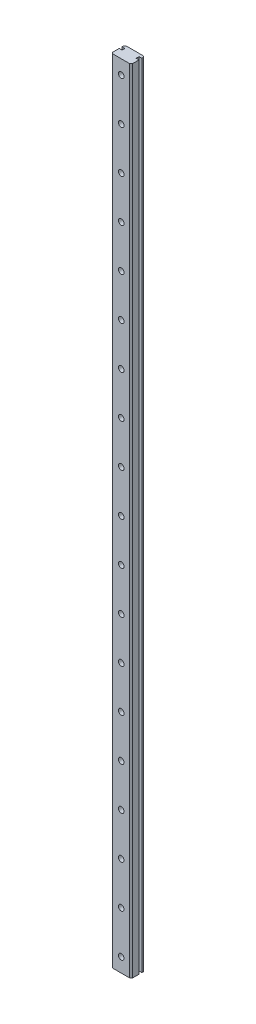
SolidWorks part; units mm, degrees
material "AISI 304"
ref_plane "前视基准面" through (0, 0, 0) normal (0, 0, 1) x (1, 0, 0)
ref_plane "上视基准面" through (0, 0, 0) normal (0, 1, 0) x (1, 0, 0)
ref_plane "右视基准面" through (0, 0, 0) normal (1, 0, 0) x (0, 0, -1)
other "Configuration Table"
sketch "草图1" plane through (0, 0, 0) normal (0, 1, 0) x (1, 0, 0)
  line L0 (0, 0) -> (0, 7.157) construction
  line L1 (-3.5, -2.4) -> (3.5, -2.4)
  line L2 (-3.5, -2.4) -> (-3.5, 2.4)
  line L3 (-3.5, 2.4) -> (3.5, 2.4)
  line L4 (3.5, -2.4) -> (3.5, 2.4)
  line L5 (-3.5, -2.4) -> (3.5, 2.4) construction
  line L6 (-3.5, 2.4) -> (3.5, -2.4) construction
  line L7 (3.5, 1.4) -> (2.5, 1.4)
  line L8 (2.5, 1.4) -> (2.5, 0.4)
  line L9 (2.5, 0.4) -> (3.5, 0.4)
  line L10 (-2.5, 0.4) -> (-3.5, 0.4)
  line L11 (-2.5, 1.4) -> (-2.5, 0.4)
  line L12 (-3.5, 1.4) -> (-2.5, 1.4)
  point P0 (0, 0)
  dimension "D1" = 7
  dimension "D2" = 4.8
  dimension "D3" = 1
  dimension "D4" = 1
  dimension "D5" = 1
extrude "凸台-拉伸1" add sketch "草图1" along normal blind 280 contours L2 L12 L11 L10 L1 L4 L9 L8 L7 L3
sketch "草图2" plane through (0, 0, -2.4) normal (0, 0, -1) x (-1, 0, 0)
  line L0 (3.5, 0) -> (-3.5, 0) construction
  line L1 (-3.5, 280) -> (-3.5, 0) construction
  circle A0 centre (0, 5) radius 1
  circle A1 centre (0, 20) radius 1
  circle A2 centre (0, 35) radius 1
  circle A3 centre (0, 50) radius 1
  circle A4 centre (0, 65) radius 1
  circle A5 centre (0, 80) radius 1
  circle A6 centre (0, 95) radius 1
  circle A7 centre (0, 110) radius 1
  circle A8 centre (0, 125) radius 1
  circle A9 centre (0, 140) radius 1
  circle A10 centre (0, 155) radius 1
  circle A11 centre (0, 170) radius 1
  circle A12 centre (0, 185) radius 1
  circle A13 centre (0, 200) radius 1
  circle A14 centre (0, 215) radius 1
  circle A15 centre (0, 230) radius 1
  circle A16 centre (0, 245) radius 1
  circle A17 centre (0, 260) radius 1
  circle A18 centre (0, 275) radius 1
  dimension "D1" = 2
  dimension "D2" = 5
  dimension "D5" = 15
  dimension "D3" = 3.5
  dimension "D4" = 19
extrude "切除-拉伸1" cut sketch "草图2" against normal blind 10
chamfer "倒角1" distance 0.5 angle 45 4 edges at (-3.5, 140, 2.4) (3.5, 140, 2.4) (-3.5, 140, -2.4) (3.5, 140, -2.4)
sketch "草图3" plane through (0, 0, -2.4) normal (0, 0, -1) x (-1, 0, 0)
  circle A0 centre (0, 5) radius 2.3833
  circle A1 centre (0, 20) radius 2.3833
  circle A2 centre (0, 35) radius 2.3833
  circle A3 centre (0, 50) radius 2.3833
  circle A4 centre (0, 65) radius 2.3833
  circle A5 centre (0, 80) radius 2.3833
  circle A6 centre (0, 95) radius 2.3833
  circle A7 centre (0, 110) radius 2.3833
  circle A8 centre (0, 125) radius 2.3833
  circle A9 centre (0, 140) radius 2.3833
  circle A10 centre (0, 155) radius 2.3833
  circle A11 centre (0, 170) radius 2.3833
  circle A12 centre (0, 185) radius 2.3833
  circle A13 centre (0, 200) radius 2.3833
  circle A14 centre (0, 215) radius 2.3833
  circle A15 centre (0, 230) radius 2.3833
  circle A16 centre (0, 245) radius 2.3833
  circle A17 centre (0, 260) radius 2.3833
  circle A18 centre (0, 275) radius 2.3833
  dimension "D1" = 4.7666
  dimension "D3" = 15
  dimension "D2" = 19
extrude "切除-拉伸2" cut sketch "草图3" against normal blind 1
